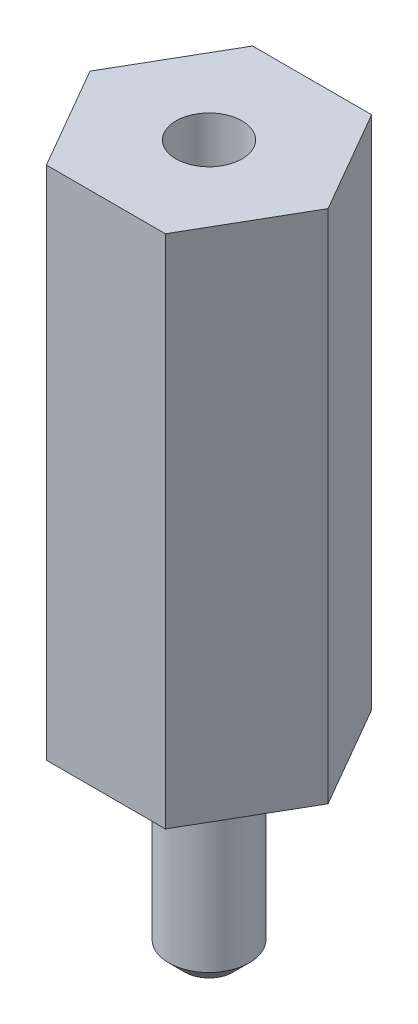
SolidWorks part; units mm, degrees
ref_plane "Front Plane" through (0, 0, 0) normal (0, 0, 1) x (1, 0, 0)
ref_plane "Top Plane" through (0, 0, 0) normal (0, 1, 0) x (1, 0, 0)
ref_plane "Right Plane" through (0, 0, 0) normal (1, 0, 0) x (0, 0, -1)
sketch "Sketch1" plane through (0, 0, 0) normal (0, 1, 0) x (1, 0, 0)
  line L1 (3.695, 0) -> (1.8475, 3.2)
  line L2 (1.8475, 3.2) -> (-1.8475, 3.2)
  line L3 (-1.8475, 3.2) -> (-3.695, 0)
  line L4 (-3.695, 0) -> (-1.8475, -3.2)
  line L5 (-1.8475, -3.2) -> (1.8475, -3.2)
  line L6 (1.8475, -3.2) -> (3.695, 0)
  circle A0 centre (0, 0) radius 3.2 construction
  dimension "D1" = 6.4
extrude "Boss-Extrude1" add sketch "Sketch1" along normal blind 16
hole_wizard "M2.5 Tapped Hole1" positions "3DSketch1" profile "Sketch2" tap size "M2.5" standard "ISO"
sketch3d "3DSketch1"
  point P0 (0, 16, 0)
sketch "Sketch2" plane through (0, 16, 0) normal (1, 0, 0) x (0, 0, 1)
  line L0 (0, 0) -> (0, 6.9659)
  line L1 (0, 6.9659) -> (1.025, 6.35)
  line L2 (1.025, 6.35) -> (1.025, 0)
  line L5 (1.025, 0) -> (0, 0)
  line L10 (0, 6.9659) -> (-1.025, 6.35) construction
  line L11 (0, -6.35) -> (0, 107.95) construction
  dimension "Tap Drill Dia." = 2.05
  dimension "Tap Drill Depth" = 6.35
  dimension "Drill Angle" = 118
cosmetic thread "Hole Thread1"
sketch "Sketch3" plane through (0, 0, 0) normal (0, -1, 0) x (1, 0, 0)
  circle A0 centre (0, 0) radius 1.25
  dimension "D1" = 2.5
extrude "Boss-Extrude2" add sketch "Sketch3" along normal blind 6
chamfer "Chamfer1" distance 0.5 angle 45 1 edges at (0, -6, -1.25)
